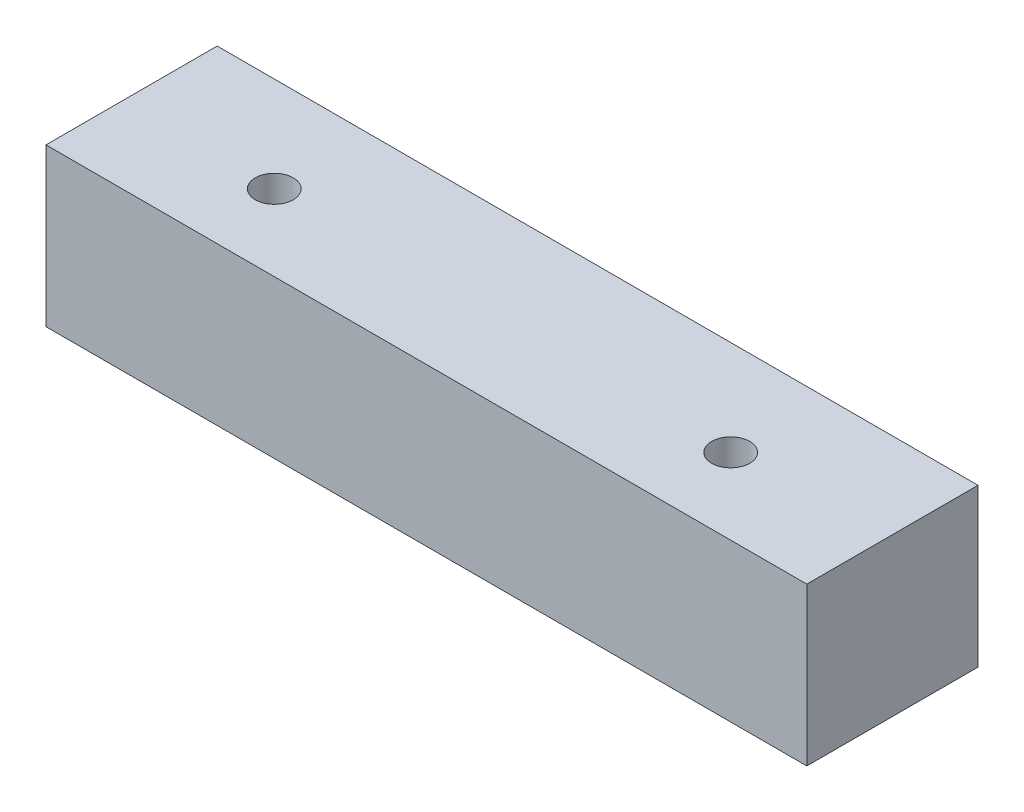
SolidWorks part; units mm, degrees
ref_plane "Front Plane" through (0, 0, 0) normal (0, 0, 1) x (1, 0, 0)
ref_plane "Top Plane" through (0, 0, 0) normal (0, 1, 0) x (1, 0, 0)
ref_plane "Right Plane" through (0, 0, 0) normal (1, 0, 0) x (0, 0, -1)
sketch "Sketch1" plane through (0, 0, 0) normal (0, 1, 0) x (1, 0, 0)
  line L0 (0, 0) -> (0, 9)
  line L1 (0, 9) -> (40, 9)
  line L2 (40, 9) -> (40, 0)
  line L3 (0, 0) -> (40, 0)
  dimension "D1" = 40
  dimension "D2" = 9
extrude "Boss-Extrude1" add sketch "Sketch1" along normal blind 8.28
sketch "Sketch2" plane through (0, 8.28, 0) normal (0, 1, 0) x (1, 0, 0)
  line L0 (0, 9) -> (8, 9)
  line L1 (40, 9) -> (0, 9) construction
  line L2 (8, 9) -> (8, 4)
  line L3 (8, 4) -> (32, 4)
  line L4 (0, 0) -> (0, 2.2) construction
  line L5 (0, 9) -> (0, 0) construction
  line L6 (0, 2.2) -> (19.4811, 2.2) construction
  line L7 (0, 2.2) -> (5, 2.2)
  line L8 (5, 2.2) -> (8, 2.2)
  line L9 (0, 0) -> (0, 0.75)
  line L10 (5, 2.2) -> (0, 0.75)
  line L11 (0, 0.75) -> (0, 2.2)
  line L12 (0, 0.75) -> (3, 0.75)
  line L13 (3, 0.75) -> (8, 2.2)
  line L14 (0, 0.75) -> (12.9505, 0.75) construction
  line L15 (16, 0.75) -> (13, 0.75)
  line L17 (8, 2.2) -> (11, 2.2)
  line L18 (8, 2.2) -> (13, 0.75)
  line L19 (11, 2.2) -> (16, 0.75)
  line L20 (24, 0.75) -> (27, 0.75)
  line L22 (40, 2.2) -> (35, 2.2)
  line L23 (40, 0) -> (40, 9) construction
  line L24 (35, 2.2) -> (32, 2.2)
  line L25 (32, 2.2) -> (29, 2.2)
  line L26 (24, 0.75) -> (29, 2.2)
  line L27 (27, 0.75) -> (32, 2.2)
  line L28 (40, 0.75) -> (37, 0.75)
  line L29 (32, 2.2) -> (37, 0.75)
  line L30 (35, 2.2) -> (40, 0.75)
  line L31 (3, 0.75) -> (13, 0.75)
  line L32 (11, 2.2) -> (16, 2.2)
  line L33 (16, 2.2) -> (16, 0)
  line L34 (0, 0) -> (40, 0) construction
  line L35 (24, 2.2) -> (29, 2.2)
  line L36 (27, 0.75) -> (37, 0.75)
  line L37 (40, 0.75) -> (40, 2.2)
  line L38 (16, 0) -> (24, 0)
  line L39 (24, 0) -> (24, 2.2)
  line L40 (16, 2.2) -> (24, 2.2)
  line L41 (16, 0.75) -> (24, 0.75)
  circle A0 centre (8, 4) radius 1
  circle A1 centre (32, 4) radius 1
  dimension "D2" = 2
  dimension "D4" = 2
  dimension "D1" = 8
  dimension "D3" = 24
  dimension "D5" = 5
  dimension "D6" = 2.2
  dimension "D7" = 0.75
  dimension "D8" = 5
  dimension "D9" = 3
  dimension "D10" = 3
  dimension "D11" = 3
  dimension "D12" = 3
  dimension "D13" = 3
  dimension "D14" = 5
  dimension "D15" = 3
  dimension "D16" = 3
  dimension "D17" = 3
  dimension "D18" = 5
  dimension "D19" = 5
extrude "Cut-Extrude1" cut sketch "Sketch2" along normal blind 5 and the other way blind 10
sketch "Sketch3" plane through (0, 0, -9) normal (0, 0, -1) x (-1, 0, 0)
  line L0 (-40, 8.28) -> (-32, 8.28) construction
  line L1 (-40, 8.28) -> (0, 8.28) construction
  line L2 (-32, 8.28) -> (-32, 4.78) construction
  line L3 (-32, 4.78) -> (-8, 4.78) construction
  line L4 (-8, 4.78) -> (-8, 8.28) construction
  line L5 (-8, 8.28) -> (0, 8.28) construction
  line L6 (-40, 8.28) -> (0, 8.28) construction
  circle A0 centre (-32, 4.78) radius 1.75
  circle A1 centre (-8, 4.78) radius 1.75
  dimension "D4" = 3.5
  dimension "D5" = 3.5
  dimension "D1" = 8
  dimension "D2" = 8
  dimension "D3" = 3.5
extrude "Cut-Extrude6" cut sketch "Sketch3" against normal blind 3.8
sketch "Sketch4" plane through (0, 0, -5.2) normal (0, 0, -1) x (-1, 0, 0)
  line L0 (-32, 4.78) -> (-33.75, 4.78) construction
  line L2 (-32, 4.78) -> (-30.25, 4.78) construction
  line L4 (-30.25, 5.03) -> (-33.25, 5.03)
  line L6 (-34.25, 4.53) -> (-30.25, 4.53)
  line L7 (-30.25, 4.53) -> (-30.25, 5.03)
  line L8 (-34.25, 4.53) -> (-33.25, 5.03)
  line L9 (-9.75, 4.78) -> (-6.25, 4.78) construction
  line L10 (-6.25, 4.53) -> (-6.25, 5.03)
  line L11 (-9.75, 4.53) -> (-9.75, 5.03)
  line L12 (-9.75, 5.03) -> (-6.25, 5.03)
  line L13 (-6.25, 4.53) -> (-9.75, 4.53)
  circle A0 centre (-32, 4.78) radius 1.75 construction
  circle A1 centre (-32, 4.78) radius 1.75 construction
  circle A2 centre (-8, 4.78) radius 1.75 construction
  circle A3 centre (-8, 4.78) radius 1.75 construction
  point P14 (-30.25, 4.78)
  point P15 (-33.75, 4.78)
  point P20 (-8, 4.78)
  point P22 (-6.25, 4.78)
  point P26 (-9.75, 4.78)
  dimension "D1" = 0.5
  dimension "D2" = 0.5
  dimension "D3" = 3
  dimension "D4" = 0.5
extrude "Cut-Extrude7" cut sketch "Sketch4" against normal blind 2.5
